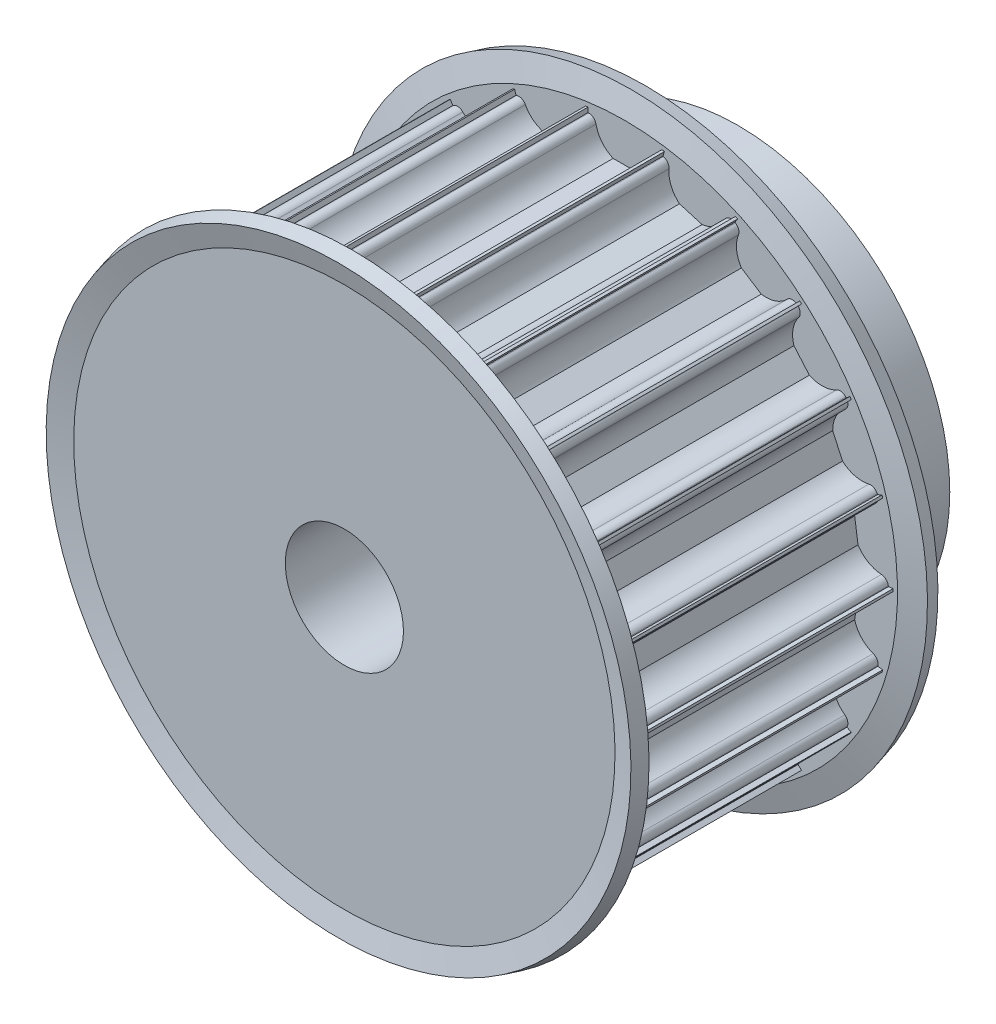
SolidWorks part; units mm, degrees
ref_plane "Front Plane" through (0, 0, 0) normal (0, 0, 1) x (1, 0, 0)
ref_plane "Top Plane" through (0, 0, 0) normal (0, 1, 0) x (1, 0, 0)
ref_plane "Right Plane" through (0, 0, 0) normal (1, 0, 0) x (0, 0, -1)
sketch "Sketch1" plane through (0, 0, 0) normal (1, 0, 0) x (0, 0, -1)
  line L0 (0, 0) -> (33.2746, 0) construction
  line L1 (0, 6) -> (40, 6)
  line L2 (40, 6) -> (40, 21.5)
  line L3 (40, 21.5) -> (30, 21.5)
  line L4 (30, 21.5) -> (30, 27.25)
  line L5 (30, 27.25) -> (0, 27.25)
  line L6 (0, 27.25) -> (0, 6)
  dimension "D1" = 27.25
  dimension "D2" = 6
  dimension "D3" = 30
  dimension "D4" = 10
  dimension "D5" = 15.5
revolve "Revolve1" add sketch "Sketch1" angle 360 about L0
sketch "Sketch2" plane through (0, 0, 0) normal (0, 0, 1) x (1, 0, 0)
  line L0 (-3.6742, 26.5) -> (-3.75, 26.5)
  line L1 (-3.75, 26.5) -> (-3.75, 28.5)
  line L2 (-3.75, 28.5) -> (3.75, 28.5)
  line L3 (3.75, 28.5) -> (3.75, 26.5)
  line L4 (3.75, 26.5) -> (3.6742, 26.5)
  line L5 (-1.199, 23.75) -> (1.199, 23.75)
  arc A0 (2.9394, 25.9) -> (1.199, 23.75) centre (0, 26.5) cw
  arc A1 (2.9394, 25.9) -> (3.6742, 26.5) centre (3.6742, 25.75) cw
  arc A2 (-2.9394, 25.9) -> (-3.6742, 26.5) centre (-3.6742, 25.75) ccw
  arc A3 (-1.199, 23.75) -> (-2.9394, 25.9) centre (0, 26.5) cw
  point P8 (0, 28.5)
  point P12 (3, 26.5)
  point P15 (-3, 26.5)
  dimension "D1" = 3
  dimension "D5" = 0.75
  dimension "D2" = 26.5
  dimension "D3" = 7.5
  dimension "D4" = 2
  dimension "D6" = 2.75
extrude "Cut-Extrude1" cut sketch "Sketch2" against normal up to next
pattern_circular "CirPattern1" count 22 over 360 about axis through (0, 0, 0) along (0, 0, 1) of "Cut-Extrude1"
sketch "Sketch4" plane through (0, 0, 0) normal (1, 0, 0) x (0, 0, -1)
  line L0 (15, 26.9539) -> (15, 14.3507) construction
  line L1 (30, 26.9539) -> (0, 26.9539) construction
  line L2 (30, 14.3507) -> (0, 14.3507) construction
  line L3 (30, 21.5) -> (30, 27.4925)
  line L4 (30, 27.4925) -> (30.592, 29.7018)
  line L5 (30.592, 29.7018) -> (29.1431, 30.09)
  line L6 (29.1431, 30.09) -> (28.5, 27.69)
  line L7 (28.5, 27.69) -> (28.5, 21.5)
  line L8 (28.5, 21.5) -> (30, 21.5)
  line L9 (40, 21.5) -> (30, 21.5) construction
  line L10 (1.5, 27.69) -> (1.5, 21.5)
  line L11 (0.8569, 30.09) -> (1.5, 27.69)
  line L12 (-0.592, 29.7018) -> (0.8569, 30.09)
  line L13 (0, 27.4925) -> (-0.592, 29.7018)
  line L14 (0, 21.5) -> (0, 27.4925)
  line L15 (1.5, 21.5) -> (0, 21.5)
  line L16 (0, 0) -> (-2.7526, 0) construction
  line L17 (0, 0.1294) -> (0, -0.1294) construction
  dimension "D1" = 15
  dimension "D2" = 1.5
  dimension "D3" = 6.19
  dimension "D4" = 2.4
revolve "Revolve2" add sketch "Sketch4" angle 360 about L16
